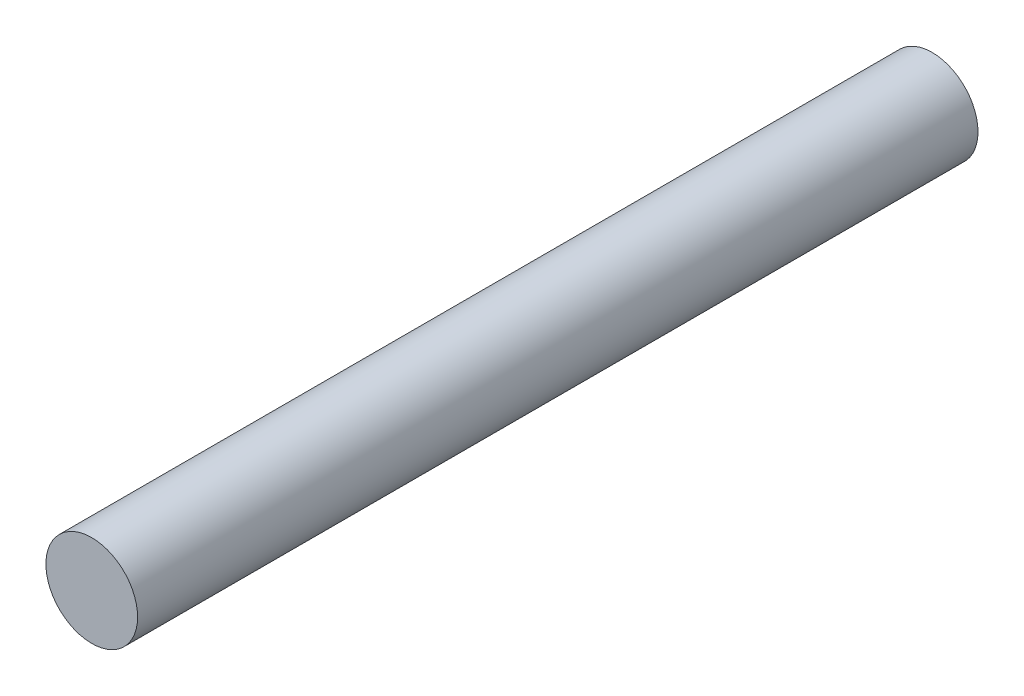
SolidWorks part; units mm, degrees
ref_plane "Plan de face" through (0, 0, 0) normal (0, 0, 1) x (1, 0, 0)
ref_plane "Plan de dessus" through (0, 0, 0) normal (0, 1, 0) x (1, 0, 0)
ref_plane "Plan de droite" through (0, 0, 0) normal (1, 0, 0) x (0, 0, -1)
sketch "Esquisse1" plane through (0, 0, 0) normal (0, 0, 1) x (1, 0, 0)
  circle A0 centre (0, 0) radius 3
  dimension "D1" = 6
extrude "Boss.-Extru.1" add sketch "Esquisse1" along normal blind 55
